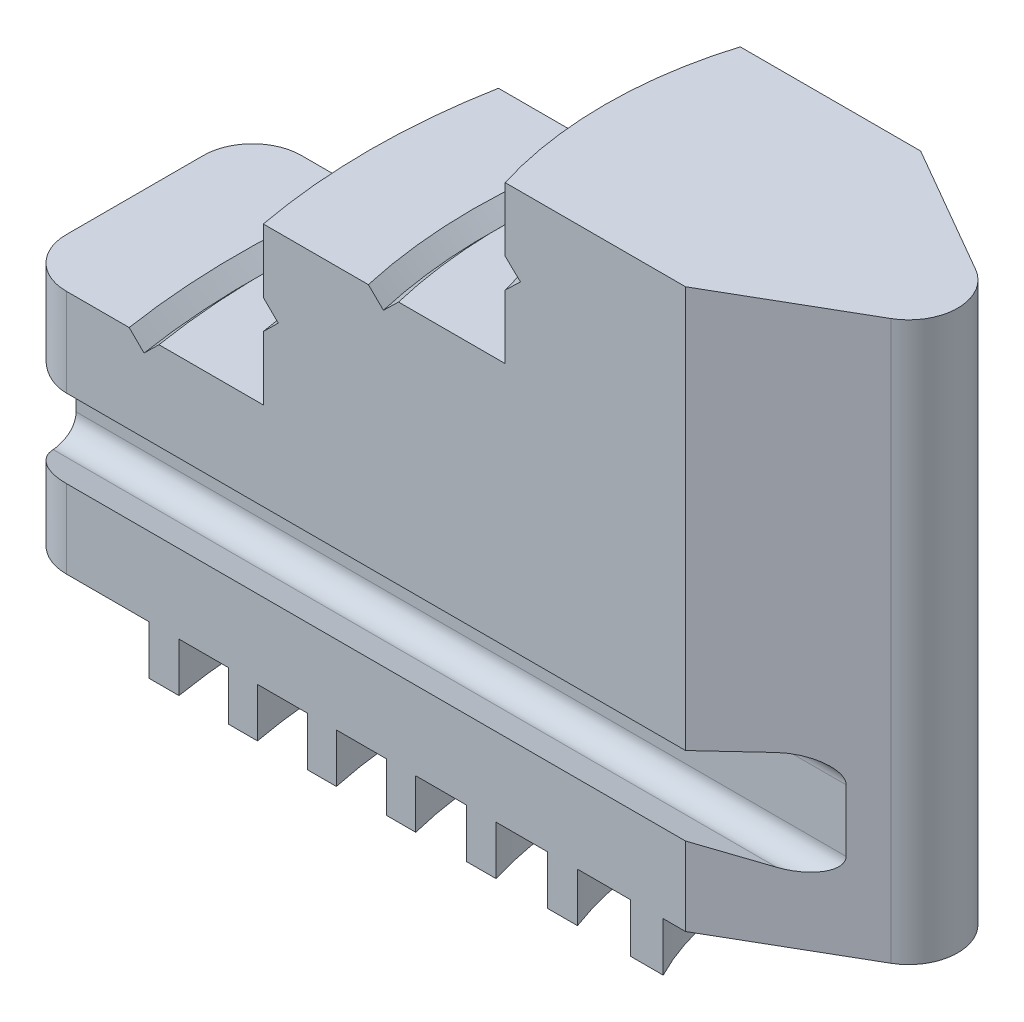
SolidWorks part; units mm, degrees
material "Alloy Steel"
ref_plane "Front Plane" through (0, 0, 0) normal (0, 0, 1) x (1, 0, 0)
ref_plane "Top Plane" through (0, 0, 0) normal (0, 1, 0) x (1, 0, 0)
ref_plane "Right Plane" through (0, 0, 0) normal (1, 0, 0) x (0, 0, -1)
sketch "Sketch1" plane through (0, 0, 0) normal (0, 1, 0) x (1, 0, 0)
  line L0 (0, 0) -> (74.1721, 0) construction
  line L1 (0, -7) -> (0, 7)
  line L2 (5, 12) -> (68.2154, 12)
  line L3 (68.2154, 12) -> (81.5, 4.3301)
  line L4 (81.5, -4.3301) -> (68.2154, -12)
  line L5 (68.2154, -12) -> (5, -12)
  line L6 (89, 3.4683) -> (89, -5.5468) construction
  arc A0 (81.5, 4.3301) -> (81.5, -4.3301) centre (79, 0) cw
  arc A1 (0, -7) -> (5, -12) centre (5, -7) ccw
  arc A2 (0, 7) -> (5, 12) centre (5, 7) cw
  point P12 (89, 0)
  point P15 (0, -12)
  point P18 (0, 12)
  dimension "D3" = 5
  dimension "D1" = 24
  dimension "D2" = 30
  dimension "D4" = 89
extrude "Boss-Extrude1" add sketch "Sketch1" along normal blind 62
sketch "Sketch2" plane through (0, 0, 0) normal (0, 0, 1) x (1, 0, 0)
  line L0 (48, 62) -> (48, 55.5)
  line L1 (5, 62) -> (68.2154, 62) construction
  line L2 (48, 55.5) -> (49.5, 54)
  line L3 (49.5, 54) -> (48, 52.5)
  line L4 (48, 52.5) -> (48, 46)
  line L5 (48, 46) -> (37.5, 46)
  line L6 (37.5, 46) -> (36, 44.5)
  line L7 (36, 44.5) -> (34.5, 46)
  line L8 (34.5, 46) -> (24, 46)
  line L9 (24, 46) -> (24, 39.5)
  line L10 (24, 39.5) -> (25.5, 38)
  line L11 (25.5, 38) -> (24, 36.5)
  line L12 (24, 36.5) -> (24, 30)
  line L13 (24, 30) -> (13.5, 30)
  line L14 (13.5, 30) -> (12, 28.5)
  line L15 (12, 28.5) -> (10.5, 30)
  line L16 (10.5, 30) -> (0, 30)
  line L17 (0, 62) -> (0, 0) construction
  line L18 (0, 30) -> (-10, 30)
  line L19 (-10, 30) -> (-10, 72)
  line L20 (-10, 72) -> (48, 72)
  line L21 (48, 72) -> (48, 62)
  line L22 (89, 71.3622) -> (89, -4.2649) construction
  line L23 (84, 0) -> (84, 62) construction
  dimension "D1" = 1.5
  dimension "D2" = 1.5
  dimension "D3" = 1.5
  dimension "D4" = 1.5
  dimension "D5" = 36
  dimension "D6" = 24
  dimension "D7" = 16
  dimension "D8" = 16
  dimension "D9" = 5
  dimension "D10" = 8
  dimension "D11" = 12
  dimension "D12" = 8
  dimension "D13" = 12
  dimension "D14" = 10
  dimension "D15" = 10
revolve "Cut-Revolve1" cut sketch "Sketch2" angle 360 about L22
sketch "Sketch5" plane through (0, 0, 0) normal (0, 0, 1) x (1, 0, 0)
  line L0 (89, 64.7808) -> (89, -3.4142) construction
  line L1 (84, 0) -> (84, 62) construction
  line L2 (89, 5) -> (63, 5)
  line L3 (63, 5) -> (63, 0)
  line L4 (5, 0) -> (68.2154, 0) construction
  line L5 (63, 0) -> (89, 0)
  line L6 (89, 0) -> (89, 5)
  line L7 (60, 0) -> (60, 5)
  line L8 (60, 5) -> (55, 5)
  line L9 (55, 5) -> (55, 0)
  line L10 (47.1036, 5) -> (47.1036, 0)
  line L11 (52.1036, 5) -> (47.1036, 5)
  line L12 (52.1036, 0) -> (52.1036, 5)
  line L13 (39.2072, 5) -> (39.2072, 0)
  line L14 (44.2072, 5) -> (39.2072, 5)
  line L15 (44.2072, 0) -> (44.2072, 5)
  line L16 (31.3108, 5) -> (31.3108, 0)
  line L17 (36.3108, 5) -> (31.3108, 5)
  line L18 (36.3108, 0) -> (36.3108, 5)
  line L19 (23.4144, 5) -> (23.4144, 0)
  line L20 (28.4144, 5) -> (23.4144, 5)
  line L21 (28.4144, 0) -> (28.4144, 5)
  line L22 (15.5179, 5) -> (15.5179, 0)
  line L23 (20.5179, 5) -> (15.5179, 5)
  line L24 (20.5179, 0) -> (20.5179, 5)
  line L25 (15.5179, 0) -> (20.5179, 0)
  line L26 (23.4144, 0) -> (28.4144, 0)
  line L27 (31.3108, 0) -> (36.3108, 0)
  line L28 (39.2072, 0) -> (44.2072, 0)
  line L29 (47.1036, 0) -> (52.1036, 0)
  line L30 (55, 0) -> (60, 0)
  line L31 (12.5179, 0) -> (12.5179, 5)
  line L32 (12.5179, 5) -> (-1.9107, 5)
  line L33 (-1.9107, 5) -> (-1.9107, 0)
  line L34 (-1.9107, 0) -> (12.5179, 0)
  dimension "D1" = 5
  dimension "D2" = 5
  dimension "D3" = 5
  dimension "D4" = 26
  dimension "D5" = 3
  dimension "D6" = 5
  dimension "D8" = 3
  dimension "D7" = 6
revolve "Cut-Revolve2" cut sketch "Sketch5" angle 360 about L0
sketch "Sketch6" plane through (0, 0, 0) normal (1, 0, 0) x (0, 0, -1)
  line L0 (-12, 13) -> (-8.6014, 11.9284)
  line L1 (-12, 62) -> (-12, 5) construction
  line L2 (-6, 13.8359) -> (-6, 20.1641)
  line L3 (-8.6014, 22.0716) -> (-12, 21)
  line L4 (-12, 21) -> (-12.9558, 20.6986)
  line L5 (-12.9558, 20.6986) -> (-12.9558, 13.3014)
  line L6 (-12, 13) -> (-12.9558, 13.3014)
  line L7 (0, 62) -> (0, -4.9078) construction
  line L8 (4.3301, 62) -> (-4.3301, 62) construction
  line L9 (6, 13.8359) -> (6, 20.1641)
  line L10 (12, 13) -> (8.6014, 11.9284)
  line L11 (12, 13) -> (12.9558, 13.3014)
  line L12 (12, 21) -> (12.9558, 20.6986)
  line L13 (12.9558, 20.6986) -> (12.9558, 13.3014)
  line L14 (8.6014, 22.0716) -> (12, 21)
  arc A0 (-8.6014, 11.9284) -> (-6, 13.8359) centre (-8, 13.8359) ccw
  arc A1 (-6, 20.1641) -> (-8.6014, 22.0716) centre (-8, 20.1641) ccw
  arc A2 (6, 20.1641) -> (8.6014, 22.0716) centre (8, 20.1641) cw
  arc A3 (8.6014, 11.9284) -> (6, 13.8359) centre (8, 13.8359) cw
  dimension "D1" = 8
  dimension "D4" = 2
  dimension "D5" = 2
  dimension "D2" = 8
  dimension "D3" = 35
  dimension "D6" = 6
extrude "Cut-Extrude1" cut sketch "Sketch6" along normal through all contours A3 L10 L11 L13 L12 L14 A2 L9 | L2 A1 L3 L4 L5 L6 L0 A0
